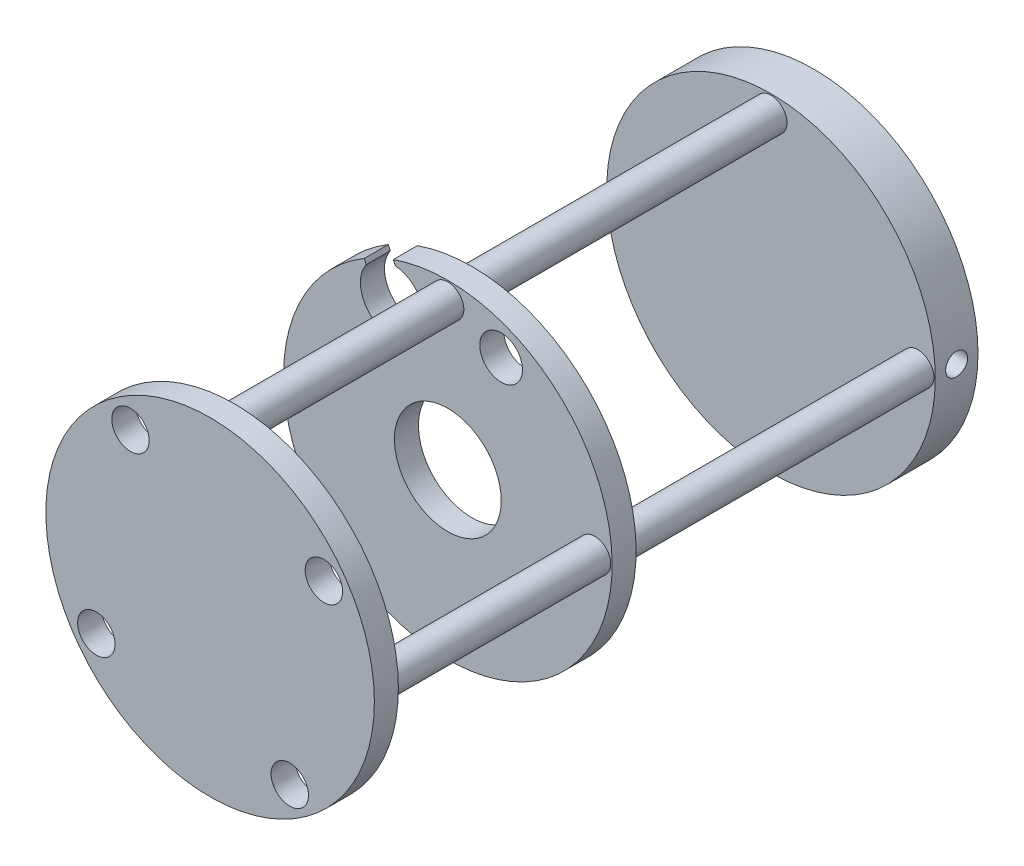
SolidWorks part; units mm, degrees
ref_plane "Plan de face" through (0, 0, 0) normal (0, 0, 1) x (1, 0, 0)
ref_plane "Plan de dessus" through (0, 0, 0) normal (0, 1, 0) x (1, 0, 0)
ref_plane "Plan de droite" through (0, 0, 0) normal (1, 0, 0) x (0, 0, -1)
sketch "Esquisse1" plane through (0, 0, 0) normal (0, 0, 1) x (1, 0, 0)
  circle A0 centre (0, 0) radius 30.75
  dimension "D1" = 61.5
extrude "Boss.-Extru.1" add sketch "Esquisse1" along normal blind 8
sketch "Esquisse2" plane through (0, 0, 8) normal (0, 0, 1) x (1, 0, 0)
  line L0 (-27.5, 0) -> (0, 0) construction
  line L1 (0, 0) -> (0, 27.5) construction
  line L2 (0, 0) -> (0, -27.5) construction
  circle A0 centre (0, 0) radius 27.5 construction
  circle A1 centre (0, 27.5) radius 3
  circle A2 centre (27.5, 0) radius 3
  circle A3 centre (-27.5, 0) radius 3
  circle A4 centre (0, -27.5) radius 3
  dimension "D2" = 55
  dimension "D3" = 6
  dimension "D1" = 90
extrude "Boss.-Extru.2" add sketch "Esquisse2" along normal blind 56
sketch "Esquisse4" plane through (0, 0, 64) normal (0, 0, 1) x (1, 0, 0)
  circle A0 centre (0, 0) radius 30.75
  dimension "D1" = 61.5
extrude "Boss.-Extru.4" add sketch "Esquisse4" along normal blind 4.5
sketch "Esquisse6" plane through (0, 0, 68.5) normal (0, 0, 1) x (1, 0, 0)
  circle A7 centre (0, -27.5) radius 3 construction
  circle A8 centre (-27.5, 0) radius 3 construction
  circle A9 centre (0, 27.5) radius 3 construction
  circle A10 centre (27.5, 0) radius 3 construction
  circle A11 centre (0, -27.5) radius 3
  circle A12 centre (-27.5, 0) radius 3
  circle A13 centre (0, 27.5) radius 3
  circle A14 centre (27.5, 0) radius 3
extrude "Boss.-Extru.5" add sketch "Esquisse6" along normal blind 40
sketch "Esquisse12" plane through (0, 0, 68.5) normal (0, 0, 1) x (1, 0, 0)
  circle A0 centre (9.9869, 23.2244) radius 4
  dimension "D1" = 8
extrude "Enlèv. mat.-Extru.1" cut sketch "Esquisse12" against normal blind 6
sketch "Esquisse13" plane through (0, 0, 68.5) normal (0, 0, 1) x (1, 0, 0)
  line L0 (0, 24.5) -> (0, 0) construction
  line L1 (0, 0) -> (-10.3541, 22.2045) construction
  line L2 (-15.6524, 26.4682) -> (-15.2691, 25.646)
  line L3 (-10.2146, 29.0039) -> (-9.8312, 28.1817)
  arc A0 (-15.2691, 25.646) -> (-9.8312, 28.1817) centre (-10.3541, 22.2045) ccw
  circle A1 centre (0, 0) radius 24.5 construction
  circle A2 centre (0, 0) radius 30.75 construction
  arc A3 (-10.2146, 29.0039) -> (-15.6524, 26.4682) centre (0, 0) ccw
  point P12 (-15.1658, 25.7889)
  dimension "D1" = 49
  dimension "D3" = 12
  dimension "D2" = 25
  dimension "D4" = 6
extrude "Enlèv. mat.-Extru.2" cut sketch "Esquisse13" against normal blind 10
sketch "Esquisse15" plane through (0, 0, 68.5) normal (0, 0, 1) x (1, 0, 0)
  circle A0 centre (0, 0) radius 10
  dimension "D1" = 20
extrude "Enlèv. mat.-Extru.3" cut sketch "Esquisse15" against normal blind 10 contours A0
sketch "Esquisse18" plane through (0, 0, 108.5) normal (0, 0, 1) x (1, 0, 0)
  circle A1 centre (0, 0) radius 30.75
  circle A2 centre (0, 0) radius 30.75
  dimension "D1" = 0
extrude "Boss.-Extru.10" add sketch "Esquisse18" along normal blind 4.5
ref_plane "Plan1" through (-30.75, 0, 0) normal (-1, 0, 0) x (0, 0, 1)
sketch "Esquisse19" plane through (-30.75, 0, 0) normal (-1, 0, 0) x (0, 0, 1)
  line L0 (0, 30.75) -> (0, -30.75) construction
  line L1 (0, -30.75) -> (8, -30.75) construction
  circle A0 centre (4, 0.25) radius 2.05
  dimension "D1" = 4.1
  dimension "D2" = 4
  dimension "D3" = 31
extrude "Enlèv. mat.-Extru.4" cut sketch "Esquisse19" against normal blind 62
sketch "Esquisse20" plane through (0, 0, 113) normal (0, 0, 1) x (1, 0, 0)
  line L0 (0, 0) -> (-14.913, 21.298) construction
  line L1 (0, 0) -> (21.298, 14.913) construction
  line L2 (0, 0) -> (0, 14.8545) construction
  circle A0 centre (0, 0) radius 30.75 construction
  circle A1 centre (21.298, 14.913) radius 3.5
  circle A2 centre (-14.913, 21.298) radius 3.5
  circle A3 centre (-21.298, -14.913) radius 3.5
  circle A4 centre (14.913, -21.298) radius 3.5
  dimension "D2" = 7
  dimension "D1" = 26
  dimension "D3" = 90
  dimension "D4" = 35
extrude "Enlèv. mat.-Extru.5" cut sketch "Esquisse20" against normal blind 10
